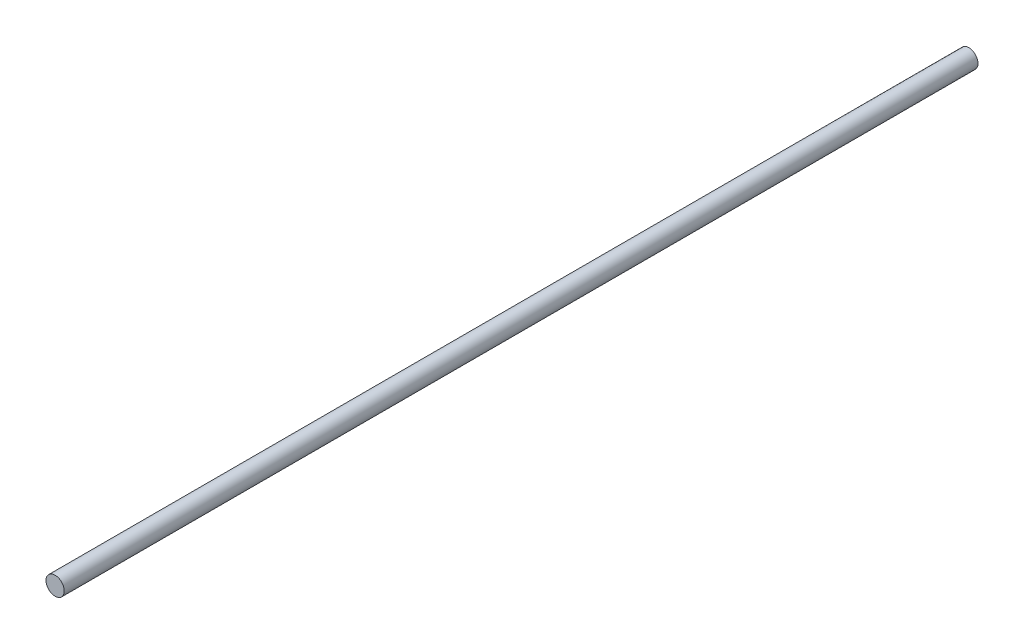
SolidWorks part; units mm, degrees
ref_plane "前视基准面" through (0, 0, 0) normal (0, 0, 1) x (1, 0, 0)
ref_plane "上视基准面" through (0, 0, 0) normal (0, 1, 0) x (1, 0, 0)
ref_plane "右视基准面" through (0, 0, 0) normal (1, 0, 0) x (0, 0, -1)
other "Configuration Table"
sketch "草图1" plane through (0, 0, 0) normal (0, 0, 1) x (1, 0, 0)
  circle A0 centre (0, 0) radius 4
  dimension "D1" = 8
extrude "凸台-拉伸1" add sketch "草图1" along normal blind 400
